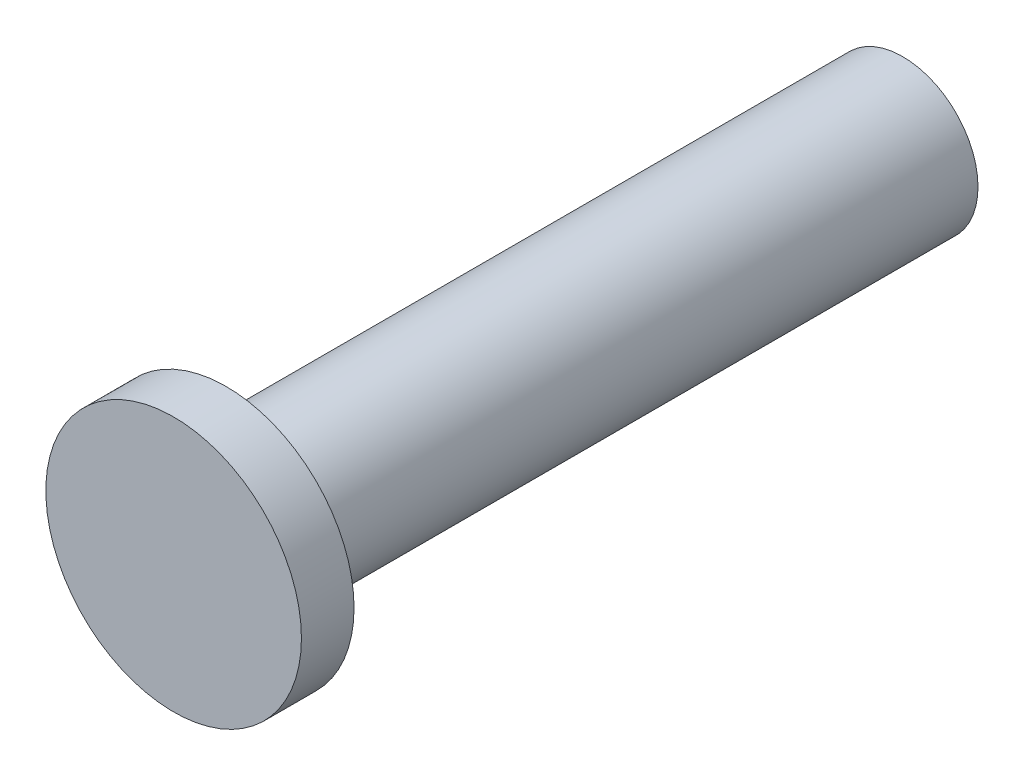
SolidWorks part; units mm, degrees
ref_plane "Front Plane" through (0, 0, 0) normal (0, 0, 1) x (1, 0, 0)
ref_plane "Top Plane" through (0, 0, 0) normal (0, 1, 0) x (1, 0, 0)
ref_plane "Right Plane" through (0, 0, 0) normal (1, 0, 0) x (0, 0, -1)
sketch "Sketch1" plane through (0, 0, 0) normal (0, 0, 1) x (1, 0, 0)
  circle A0 centre (0, 0) radius 1
extrude "Thread_Envelope" add sketch "Sketch1" along normal blind 9 from offset 9
sketch "Sketch2" plane through (0, 0, 0) normal (0, 0, 1) x (1, 0, 0)
  circle A0 centre (0, 0) radius 1.7
extrude "Head_Envelope" add sketch "Sketch2" along normal blind 0.7
